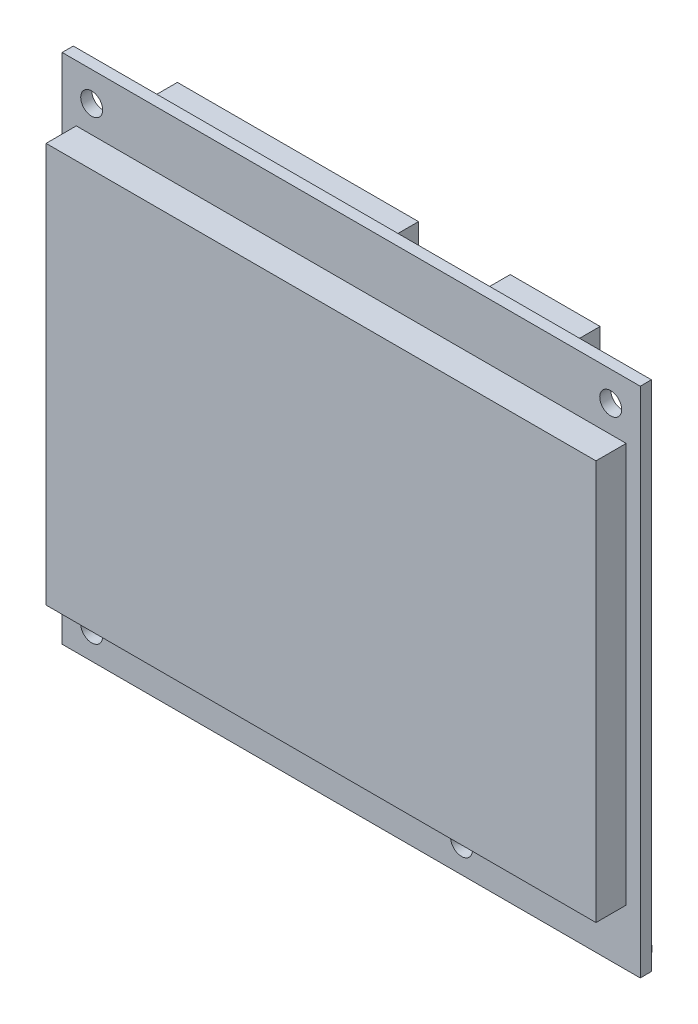
SolidWorks part; units mm, degrees
ref_plane "Front Plane" through (0, 0, 0) normal (0, 0, 1) x (1, 0, 0)
ref_plane "Top Plane" through (0, 0, 0) normal (0, 1, 0) x (1, 0, 0)
ref_plane "Right Plane" through (0, 0, 0) normal (1, 0, 0) x (0, 0, -1)
sketch "Sketch1" plane through (0, 0, 0) normal (0, 0, -1) x (-1, 0, 0)
  line L1 (-32.25, -24.25) -> (32.25, -24.25) construction
  line L2 (-32.25, -24.25) -> (-32.25, 24.25) construction
  line L3 (-32.25, 24.25) -> (32.25, 24.25) construction
  line L4 (32.25, -24.25) -> (32.25, 24.25) construction
  line L5 (-32.25, -24.25) -> (32.25, 24.25) construction
  line L6 (-32.25, 24.25) -> (32.25, -24.25) construction
  line L7 (-36, 28) -> (41.7, 28) construction
  line L8 (-36, 28) -> (-36, -28.5) construction
  line L9 (-36, -28.5) -> (41.7, -28.5) construction
  line L10 (41.7, 28) -> (41.7, -28.5) construction
  line L11 (-37.9864, 35.9904) -> (43.7, 35.9904)
  line L12 (-37.9864, 35.9904) -> (-37.9864, -36.425)
  line L13 (-37.9864, -36.425) -> (43.7, -36.425)
  line L14 (43.7, 35.9904) -> (43.7, -36.425)
  point P0 (0, 0)
  dimension "D1" = 64.5
  dimension "D2" = 48.5
  dimension "D3" = 3.75
  dimension "D4" = 3.75
  dimension "D5" = 56.5
  dimension "D6" = 77.7
  dimension "D7" = 7.925
  dimension "D8" = 72.4154
  dimension "D9" = 81.6864
  dimension "D10" = 2
extrude "Boss-Extrude1" add sketch "Sketch1" along normal blind 1.5748
sketch "Sketch2" plane through (0, 0, 0) normal (0, 0, -1) x (-1, 0, 0)
  line L1 (-36, -28.5) -> (41.7, -28.5)
  line L2 (-36, -28.5) -> (-36, 28)
  line L3 (-36, 28) -> (41.7, 28)
  line L4 (41.7, -28.5) -> (41.7, 28)
  line L5 (41.7, 28) -> (49.6841, 28) construction
  line L6 (-36, 28) -> (-43.9841, 28) construction
  line L10 (-32.25, -24.25) -> (32.25, -24.25) construction
  line L11 (-32.25, -24.25) -> (-32.25, 24.25) construction
  line L12 (-32.25, 24.25) -> (32.25, 24.25) construction
  line L13 (32.25, -24.25) -> (32.25, 24.25) construction
  line L14 (-32.25, -24.25) -> (32.25, 24.25) construction
  line L15 (-32.25, 24.25) -> (32.25, -24.25) construction
  point P0 (0, 0)
  point P14 (0, 0)
  dimension "D1" = 56.5
  dimension "D2" = 77.7
  dimension "D3" = 3.75
  dimension "D4" = 48.5
  dimension "D5" = 64.5
  dimension "D6" = 3.75
extrude "Boss-Extrude2" add sketch "Sketch2" against normal blind 4.27
sketch "Sketch3" plane through (0, 0, -1.5748) normal (0, 0, 1) x (1, 0, 0)
  line L1 (25.66, 33.8141) -> (12.96, 33.8141)
  line L2 (25.66, 33.8141) -> (25.66, 28.7341)
  line L3 (25.66, 28.7341) -> (12.96, 28.7341)
  line L4 (12.96, 33.8141) -> (12.96, 28.7341)
  line L6 (0, 33.8141) -> (-34.0711, 33.8141)
  line L7 (0, 33.8141) -> (0, 28.7341)
  line L8 (0, 28.7341) -> (-34.0711, 28.7341)
  line L9 (-34.0711, 33.8141) -> (-34.0711, 28.7341)
  line L10 (-34.0711, -29.1593) -> (0, -29.1593)
  line L11 (-34.0711, -29.1593) -> (-34.0711, -34.2393)
  line L12 (-34.0711, -34.2393) -> (0, -34.2393)
  line L13 (0, -29.1593) -> (0, -34.2393)
  dimension "D1" = 5.08
  dimension "D2" = 12.7
sketch "Sketch4" plane through (0, 0, -1.5748) normal (0, 0, -1) x (-1, 0, 0)
  line L0 (43.7, 35.9904) -> (-37.9864, 35.9904) construction
  line L1 (-37.9864, 35.9904) -> (-37.9864, -36.425) construction
  line L2 (43.7, -36.425) -> (43.7, 35.9904) construction
  line L3 (-37.9864, -36.425) -> (43.7, -36.425) construction
  circle A0 centre (39.525, 31.8154) radius 1.55
  circle A1 centre (39.525, -32.625) radius 1.55
  circle A2 centre (-12.735, -32.625) radius 1.55
  circle A3 centre (-33.8114, 31.8154) radius 1.55
  dimension "D3" = 3.1
  dimension "D1" = 4.175
  dimension "D2" = 4.175
  dimension "D4" = 4.175
  dimension "D5" = 3.8
  dimension "D6" = 52.26
extrude "Cut-Extrude1" cut sketch "Sketch4" against normal through all
extrude "Boss-Extrude3" add sketch "Sketch3" against normal blind 5.08
sketch "Sketch5" plane through (0, 0, -1.5748) normal (0, 0, -1) x (-1, 0, 0)
  line L0 (19.4766, 13.5356) -> (30.7313, 2.2809)
  line L1 (30.7313, 2.2809) -> (19.4766, -8.9738)
  line L2 (19.4766, -8.9738) -> (8.2218, 2.2809)
  line L3 (8.2218, 2.2809) -> (19.4766, 13.5356)
  line L5 (-15.8477, -24.7973) -> (-26.991, -24.7973)
  line L6 (-15.8477, -24.7973) -> (-15.8477, -9.9767)
  line L7 (-15.8477, -9.9767) -> (-26.991, -9.9767)
  line L8 (-26.991, -24.7973) -> (-26.991, -9.9767)
  line L9 (-37.0611, -34.1253) -> (-31.3584, -34.1253)
  line L10 (-37.0611, -34.1253) -> (-37.0611, -35.0607)
  line L11 (-37.0611, -35.0607) -> (-31.3584, -35.0607)
  line L12 (-31.3584, -34.1253) -> (-31.3584, -35.0607)
extrude "Boss-Extrude4" add sketch "Sketch5" along normal blind 1
